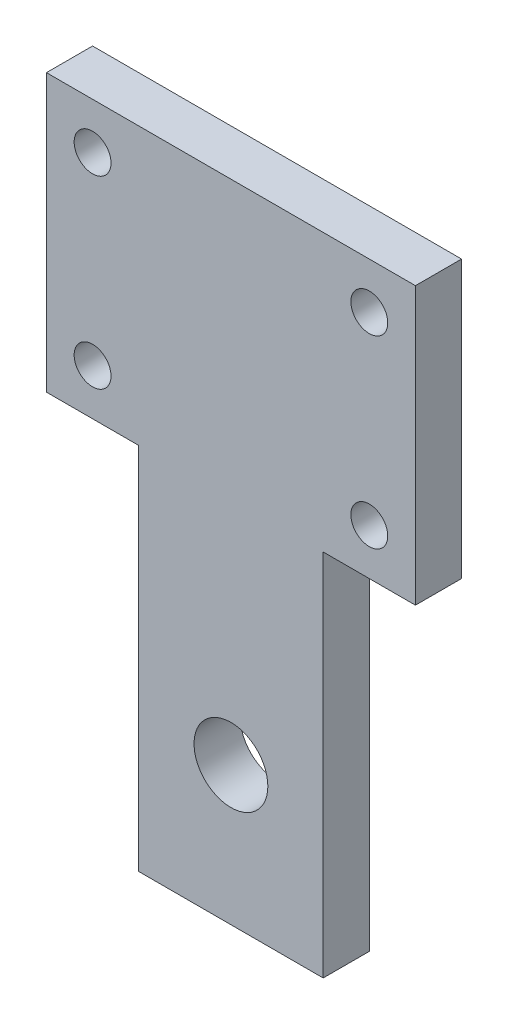
SolidWorks part; units mm, degrees
material "Acrylic (Medium-high impact)"
ref_plane "Front Plane" through (0, 0, 0) normal (0, 0, 1) x (1, 0, 0)
ref_plane "Top Plane" through (0, 0, 0) normal (0, 1, 0) x (1, 0, 0)
ref_plane "Right Plane" through (0, 0, 0) normal (1, 0, 0) x (0, 0, -1)
sketch "Sketch1" plane through (0, 0, 0) normal (0, 0, 1) x (1, 0, 0)
  line L0 (-20, 30) -> (-20, 0)
  line L1 (-20, 0) -> (-10, 0)
  line L2 (-10, 0) -> (-10, -40)
  line L3 (-10, -40) -> (10, -40)
  line L4 (10, -40) -> (10, 0)
  line L5 (10, 0) -> (20, 0)
  line L6 (20, 0) -> (20, 30)
  line L7 (20, 30) -> (-20, 30)
  line L8 (0, 0) -> (0, -94.2763) construction
  dimension "D1" = 40
  dimension "D2" = 20
  dimension "D3" = 30
  dimension "D4" = 40
extrude "Boss-Extrude1" add sketch "Sketch1" along normal mid plane 5
sketch "Sketch2" plane through (0, 0, 2.5) normal (0, 0, 1) x (1, 0, 0)
  line L0 (20, 30) -> (-20, 30) construction
  line L1 (-10, -40) -> (10, -40) construction
  circle A0 centre (-25, 20) radius 2.5
  circle A1 centre (25, 20) radius 2.5
  circle A2 centre (0, -25) radius 4
  dimension "D1" = 5
  dimension "D5" = 8
  dimension "D2" = 50
  dimension "D3" = 25
  dimension "D4" = 10
  dimension "D6" = 15
extrude "Cut-Extrude1" cut sketch "Sketch2" against normal through all
sketch "Sketch3" plane through (0, 0, 2.5) normal (0, 0, 1) x (1, 0, 0)
  line L0 (-20, 15) -> (20, 15) construction
  line L1 (-20, 30) -> (-20, 0) construction
  line L2 (20, 0) -> (20, 30) construction
  circle A0 centre (-15, 25) radius 2
  circle A1 centre (15, 25) radius 2
  circle A2 centre (15, 5) radius 2
  circle A3 centre (-15, 5) radius 2
  dimension "D1" = 4
  dimension "D2" = 30
  dimension "D3" = 20
  dimension "D4" = 15
extrude "Cut-Extrude2" cut sketch "Sketch3" against normal blind 10
